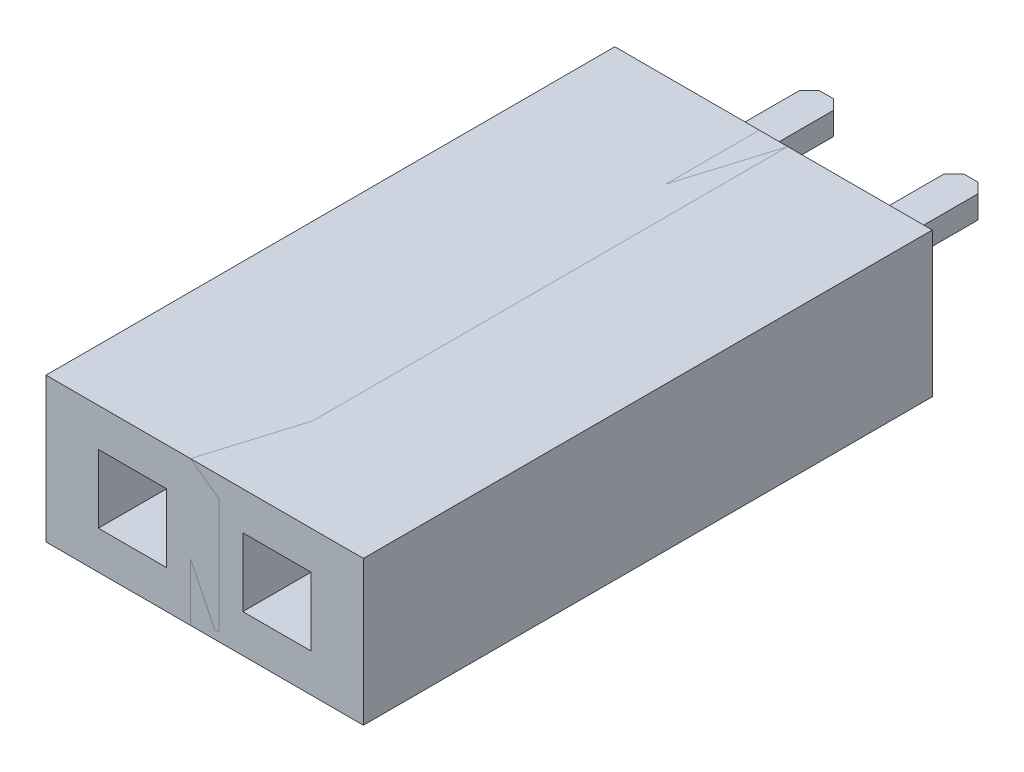
SolidWorks part; units mm, degrees
ref_plane "Front Plane" through (0, 0, 0) normal (0, 0, 1) x (1, 0, 0)
ref_plane "Top Plane" through (0, 0, 0) normal (0, 1, 0) x (1, 0, 0)
ref_plane "Right Plane" through (0, 0, 0) normal (1, 0, 0) x (0, 0, -1)
sketch "Sketch1" plane through (0, 0, 0) normal (1, 0, 0) x (0, -1, 0)
  line L1 (-1.27, 0) -> (1.27, 0)
  line L2 (-1.27, 0) -> (-1.27, -10)
  line L3 (-1.27, -10) -> (1.27, -10)
  line L4 (1.27, 0) -> (1.27, -10)
  line L5 (-1.27, 0) -> (1.27, -10) construction
  line L6 (-1.27, -10) -> (1.27, 0) construction
  point P0 (0, -5)
  point P6 (0, 0)
  dimension "D1" = 2.54
  dimension "D2" = 10
extrude "Boss-Extrude1" add sketch "Sketch1" along normal mid plane 3.04
sketch "Sketch2" plane through (0, 0, 10) normal (0, 0, 1) x (-1, 0, 0)
  line L0 (0, -1.27) -> (0, 1.27) construction
  line L3 (-1.52, -1.27) -> (1.52, -1.27) construction
  line L4 (-0.6, 0.6) -> (0.6, 0.6)
  line L5 (-0.6, 0.6) -> (-0.6, -0.6)
  line L6 (-0.6, -0.6) -> (0.6, -0.6)
  line L7 (0.6, 0.6) -> (0.6, -0.6)
  line L8 (-0.6, 0.6) -> (0.6, -0.6) construction
  line L9 (-0.6, -0.6) -> (0.6, 0.6) construction
  line L10 (-1.52, 1.27) -> (1.52, 1.27) construction
  point P5 (0, 0)
  dimension "D1" = 1.2
extrude "Cut-Extrude1" cut sketch "Sketch2" against normal blind 7
sketch "Sketch3" plane through (0, 0, 0) normal (0, 1, 0) x (1, 0, 0)
  line L0 (-0.3, 0) -> (-0.3, 2.0243)
  line L2 (-0.3, 2.0243) -> (-0.1243, 2.2)
  line L3 (-0.1243, 2.2) -> (0.1243, 2.2)
  line L4 (0, 2.2) -> (0, 0) construction
  line L5 (-0.3, 0) -> (0.3, 0)
  line L6 (0.3, 2.0243) -> (0.1243, 2.2)
  line L7 (0.3, 0) -> (0.3, 2.0243)
  dimension "D1" = 0.6
  dimension "D2" = 45
  dimension "D3" = 2.2
extrude "Boss-Extrude2" add sketch "Sketch3" along normal mid plane 0.4
pattern_linear "LPattern1" count 2 spacing 2.54 along (1, 0, 0) of bodies 103
